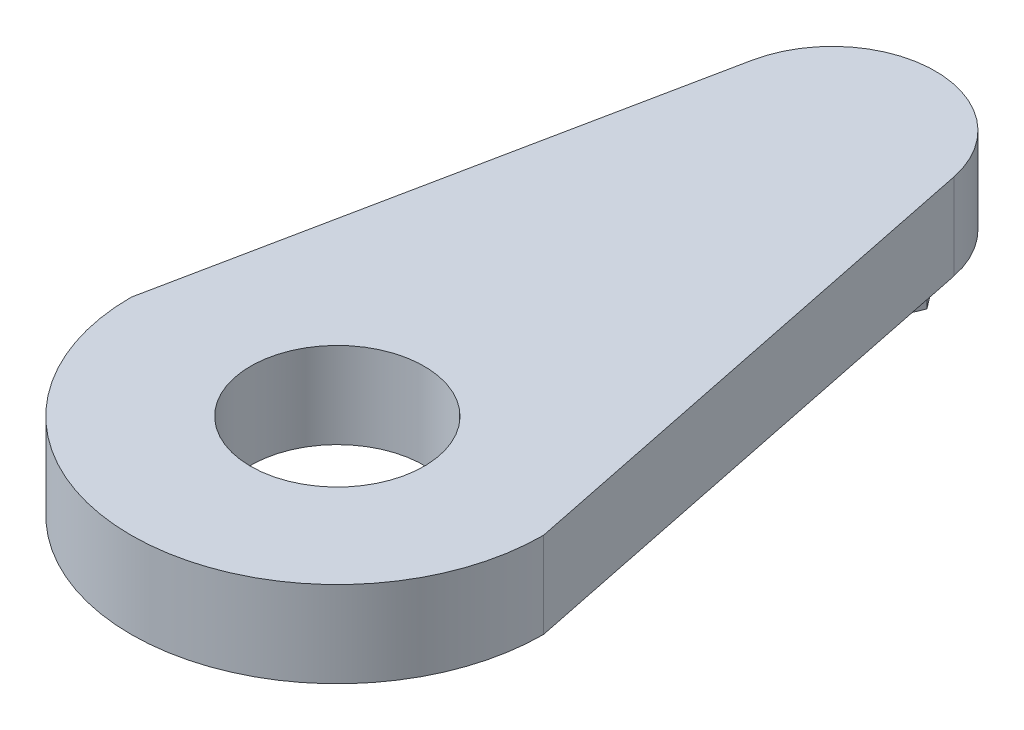
SolidWorks part; units mm, degrees
material "ABS"
ref_plane "Front Plane" through (0, 0, 0) normal (0, 0, 1) x (1, 0, 0)
ref_plane "Top Plane" through (0, 0, 0) normal (0, 1, 0) x (1, 0, 0)
ref_plane "Right Plane" through (0, 0, 0) normal (1, 0, 0) x (0, 0, -1)
sketch "Sketch1" plane through (0, 0, 0) normal (0, 1, 0) x (1, 0, 0)
  line L0 (-6, 0) -> (-2.9394, 15)
  line L1 (2.9394, 15) -> (6, 0)
  line L2 (0, 0) -> (0, 9.6546) construction
  circle A0 centre (0, 0) radius 2.525
  arc A1 (-5.5204, 2.3506) -> (5.5204, 2.3506) centre (0, 0) ccw
  arc A2 (-2.9394, 15) -> (2.9394, 15) centre (0, 14.4002) cw
  dimension "D1" = 5.05
  dimension "D2" = 12
  dimension "D4" = 3
  dimension "D3" = 15
extrude "Boss-Extrude1" add sketch "Sketch1" along normal blind 2.5
sketch "Sketch2" plane through (0, 0, 0) normal (0, -1, 0) x (1, 0, 0)
  circle A0 centre (0, -15.039) radius 1.0406
extrude "Boss-Extrude2" add sketch "Sketch2" along normal blind 1
sketch "Sketch3" plane through (0, -1, 0) normal (0, -1, 0) x (1, 0, 0)
  line L1 (1.1474, -13.5369) -> (-0.7272, -13.2943)
  line L2 (-0.7272, -13.2943) -> (-1.8745, -14.7964)
  line L3 (-1.8745, -14.7964) -> (-1.1474, -16.5411)
  line L4 (-1.1474, -16.5411) -> (0.7272, -16.7837)
  line L5 (0.7272, -16.7837) -> (1.8745, -15.2816)
  line L6 (1.8745, -15.2816) -> (1.1474, -13.5369)
  circle A0 centre (0, -15.039) radius 1.6369 construction
extrude "Boss-Extrude3" add sketch "Sketch3" along normal blind 0.5
